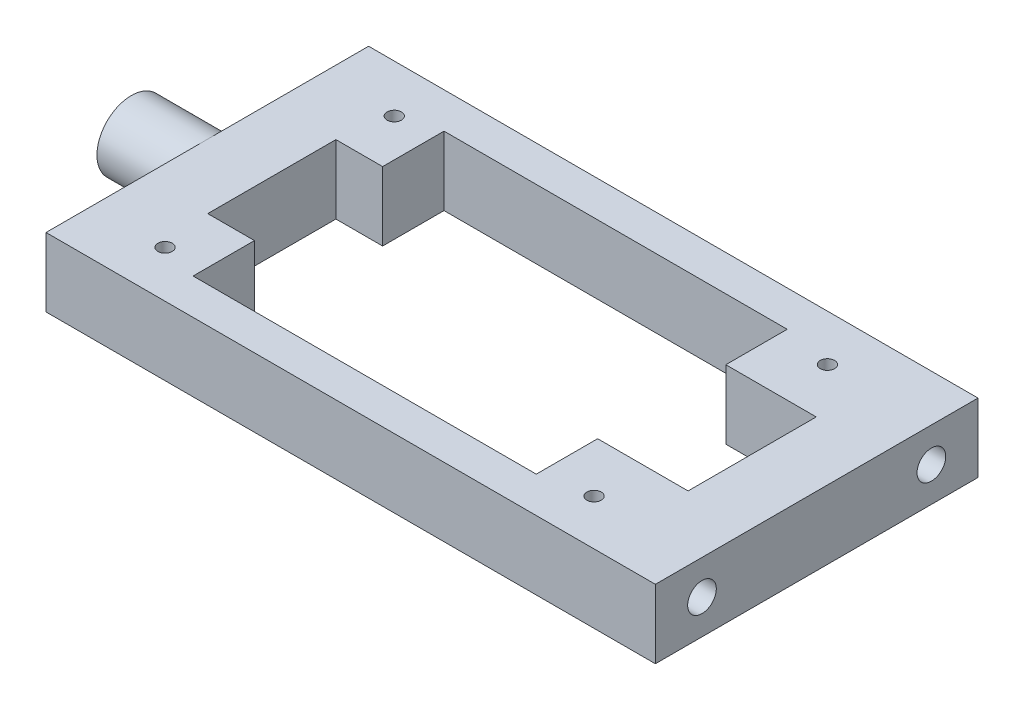
SolidWorks part; units mm, degrees
material "Prusament PETG"
ref_plane "Front Plane" through (0, 0, 0) normal (0, 0, 1) x (1, 0, 0)
ref_plane "Top Plane" through (0, 0, 0) normal (0, 1, 0) x (1, 0, 0)
ref_plane "Right Plane" through (0, 0, 0) normal (1, 0, 0) x (0, 0, -1)
sketch "Sketch1" plane through (0, 0, 0) normal (0, 0, 1) x (1, 0, 0)
  line L0 (0, 0) -> (0, 3.2946) construction
  line L1 (0, 0) -> (-16.8158, 0) construction
  line L6 (-32.9129, 10) -> (-22.9129, 10)
  line L7 (-32.9129, -10) -> (-22.9129, -10)
  arc A0 (-22.9129, 10) -> (-22.9129, -10) centre (0, 0) ccw
  arc A1 (-32.9129, 10) -> (-32.9129, -10) centre (0, 0) ccw
  dimension "D1" = 25
  dimension "D2" = 10
  dimension "D3" = 20
revolve "Revolve1" add sketch "Sketch1" angle 360 about L0
ref_plane "Plane1" through (34.3985, 0, 0) normal (1, 0, 0) x (0, 0, -1)
ref_plane "Plane2" through (49.3985, 0, 0) normal (1, 0, 0) x (0, 0, -1)
sketch "Sketch4" plane through (49.3985, 0, 0) normal (1, 0, 0) x (0, 0, -1)
  circle A0 centre (0, 0) radius 5
  dimension "D1" = 10
sketch "Sketch7" plane through (0, 0, 0) normal (0, 0, 1) x (1, 0, 0)
  line L0 (0, 0) -> (0, 26.9064) construction
  line L1 (0, 0) -> (-95.8603, 0) construction
  line L2 (0, 60) -> (0, 50)
  line L3 (0, -50) -> (0, -60)
  arc A0 (0, 50) -> (0, -50) centre (0, 0) ccw
  arc A1 (0, 60) -> (0, -60) centre (0, 0) ccw
  dimension "D2" = 10
  dimension "D1" = 50
sketch "Sketch8" plane through (0, -10, 0) normal (0, -1, 0) x (1, 0, 0)
  circle A0 centre (0, 0) radius 35
  dimension "D1" = 70
extrude "Boss-Extrude3" add sketch "Sketch8" along normal blind 1
sketch "Sketch9" plane through (0, 0, 0) normal (1, 0, 0) x (0, 0, -1)
  circle A0 centre (0, 0) radius 5
  dimension "D1" = 10
extrude "Boss-Extrude4" add sketch "Sketch9" along normal blind 60 and the other way up to surface
sketch "Sketch10" plane through (60, 0, 0) normal (1, 0, 0) x (0, 0, -1)
  circle A0 centre (0, 0) radius 4
ref_plane "Plane3" through (39.2087, 0, 0) normal (-1, 0, 0) x (0, 0, 1)
extrude "Cut-Extrude2" cut sketch "Sketch10" against normal up to surface (20.7913 mm away)
ref_plane "Plane4" through (0, 0.1888, -4.9964) normal (0, 0.0378, -0.9993) x (-1, 0, 0)
sketch "Sketch11" plane through (0, 0.1888, -4.9964) normal (0, 0.0378, -0.9993) x (-1, 0, 0)
  circle A0 centre (-55, 0) radius 5 construction
  circle A1 centre (-55, 0) radius 1.5
  dimension "D1" = 3
extrude "Cut-Extrude3" cut sketch "Sketch11" against normal through all
sketch "Sketch12" plane through (0, -11, 0) normal (0, -1, 0) x (1, 0, 0)
  line L4 (-43, -22.5) -> (-43, 22.5)
  line L5 (-43, -22.5) -> (-16.3848, -22.5)
  line L6 (-43, 22.5) -> (-16.8415, 22.5)
  line L7 (35, -22.5) -> (35, 22.5)
  line L8 (-35, 0) -> (35, 0) construction
  line L9 (-16.3848, -28.9013) -> (16.3848, -28.9013)
  line L11 (-16.8415, 22.5) -> (-16.8415, 28.9866)
  line L12 (-16.8415, 28.9866) -> (16.8415, 28.9866)
  line L13 (16.8415, 22.5) -> (16.8415, 28.9866)
  line L14 (-16.3848, -28.9013) -> (-16.3848, -22.5)
  line L16 (16.3848, -28.9013) -> (16.3848, -22.5)
  line L17 (16.8415, 22.5) -> (35, 22.5)
  line L18 (16.3848, -22.5) -> (35, -22.5)
  point P0 (-32.9035, 15.9936)
  point P1 (-32.9035, -16.0064)
  point P2 (27.0965, -16.0064)
  point P4 (27.0965, 15.9936)
  point P29 (0, 0)
  dimension "D1" = 78
  dimension "D2" = 45
extrude "Boss-Extrude5" add sketch "Sketch12" against normal up to surface (21 mm away) up to face at (0, 10, -32.9129)
sketch "Sketch13" plane through (-43, 0, 0) normal (-1, 0, 0) x (0, 0, 1)
  line L1 (44.4415, -11) -> (-44.4415, -11)
  line L2 (44.4415, -11) -> (44.4415, -5.4642)
  line L3 (44.4415, -5.4642) -> (-44.4415, -5.4642)
  line L4 (-44.4415, -11) -> (-44.4415, -5.4642)
  line L5 (22.5, -11) -> (-22.5, -11) construction
  line L6 (0, -11) -> (0, -5.4642) construction
  line L7 (0, -5.4642) -> (0, 10) construction
  line L8 (-22.5, 10) -> (22.5, 10) construction
  line L9 (0, 0) -> (-22.5, 0) construction
  line L10 (-22.5, 10) -> (-22.5, -10) construction
  line L11 (44.4415, 5.4642) -> (-44.4415, 5.4642)
  line L12 (-44.4415, 11) -> (-44.4415, 5.4642)
  line L13 (44.4415, 11) -> (-44.4415, 11)
  line L14 (44.4415, 11) -> (44.4415, 5.4642)
extrude "Cut-Extrude4" cut sketch "Sketch13" against normal through all
sketch "Sketch14" plane through (0, -5.4642, 0) normal (0, -1, 0) x (1, 0, 0)
  line L1 (27.0965, 15.9936) -> (-32.9035, 15.9936) construction
  line L2 (27.0965, 15.9936) -> (27.0965, -16.0064) construction
  line L3 (27.0965, -16.0064) -> (-32.9035, -16.0064) construction
  line L4 (-32.9035, 15.9936) -> (-32.9035, -16.0064) construction
  circle A0 centre (-32.9035, 15.9936) radius 1
  circle A1 centre (-32.7795, -15.854) radius 1
  circle A2 centre (27.0682, 16.122) radius 1
  circle A3 centre (27.45, -16.0449) radius 1
  dimension "D3" = 2
  dimension "D4" = 2
  dimension "D5" = 2
  dimension "D6" = 2
  dimension "D1" = 60
  dimension "D2" = 32
extrude "Cut-Extrude5" cut sketch "Sketch14" against normal through all
sketch "Sketch15" plane through (-43, 0, 0) normal (-1, 0, 0) x (0, 0, 1)
  line L1 (-37.9637, 5.4642) -> (37.2025, 5.4642)
  line L2 (-37.9637, 5.4642) -> (-37.9637, 5)
  line L3 (-37.9637, 5) -> (37.2025, 5)
  line L4 (37.2025, 5.4642) -> (37.2025, 5)
  line L5 (-37.6637, -5) -> (37.8003, -5)
  line L6 (-37.6637, -5) -> (-37.6637, -5.4642)
  line L7 (-37.6637, -5.4642) -> (37.8003, -5.4642)
  line L8 (37.8003, -5) -> (37.8003, -5.4642)
  line L9 (22.5, -5.4642) -> (-22.5, -5.4642) construction
  circle A0 centre (0, 0) radius 5 construction
  circle A1 centre (0, 0) radius 5 construction
extrude "Cut-Extrude6" cut sketch "Sketch15" against normal through all
sketch "Sketch16" plane through (-43, 0, 0) normal (-1, 0, 0) x (0, 0, 1)
  line L0 (22.5, 5) -> (22.5, -5) construction
  line L1 (-38.0201, 5) -> (36.8636, 5)
  line L2 (-38.0201, 5) -> (-38.0201, 4.8)
  line L3 (-38.0201, 4.8) -> (36.8636, 4.8)
  line L4 (36.8636, 5) -> (36.8636, 4.8)
  line L5 (-22.5, 0) -> (22.5, 0) construction
  line L6 (-22.5, 5) -> (-22.5, -5) construction
  line L7 (36.8636, -5) -> (36.8636, -4.8)
  line L8 (-38.0201, -5) -> (-38.0201, -4.8)
  line L9 (-38.0201, -5) -> (36.8636, -5)
  line L10 (-38.0201, -4.8) -> (36.8636, -4.8)
  line L11 (-22.5, 5) -> (-34.0332, 5) construction
  dimension "D1" = 0.2
extrude "Cut-Extrude7" cut sketch "Sketch16" against normal through all both and the other way through all
sketch "Sketch17" plane through (35, 0, 0) normal (1, 0, 0) x (0, 0, -1)
  line L0 (22.5, -4.8) -> (-22.5, -4.8)
  line L1 (22.5, -4.8) -> (22.5, 4.8706)
  line L2 (-22.5, -4.8) -> (-22.5, 4.8706)
  line L3 (22.5, 4.8706) -> (-22.5, 4.8706)
extrude "Cut-Extrude8" cut sketch "Sketch17" along normal up to surface (25 mm away) up to face at (60, 0, 0)
sketch "Sketch18" plane through (35, 0, 0) normal (1, 0, 0) x (0, 0, -1)
  line L0 (22.5, -4.8) -> (22.5, 4.8)
  line L1 (22.5, -4.8) -> (-22.6662, -4.8)
  line L2 (22.5, 4.8) -> (-22.6662, 4.8)
  line L3 (-22.6662, -4.8) -> (-22.6662, 4.8)
extrude "Boss-Extrude6" add sketch "Sketch18" along normal blind 7
sketch "Sketch19" plane through (42, 0, 0) normal (1, 0, 0) x (0, 0, -1)
  circle A0 centre (-16, 0.0112) radius 2
  circle A1 centre (16, 0.0112) radius 2
  dimension "D1" = 4
extrude "Cut-Extrude9" cut sketch "Sketch19" against normal blind 8.2
sketch "Sketch20" plane through (0, 4.8, 0) normal (0, 1, 0) x (1, 0, 0)
  line L0 (42, 22.5) -> (-43, 22.5)
  line L1 (42, 22.5) -> (42, 35.5488)
  line L2 (-43, 22.5) -> (-43, 35.5488)
  line L3 (42, 35.5488) -> (-43, 35.5488)
  line L4 (42.0002, -22.5) -> (-43, -22.5)
  line L5 (42.0002, -22.5) -> (42.0002, -36.4253)
  line L6 (-43, -22.5) -> (-43, -36.4253)
  line L7 (42.0002, -36.4253) -> (-43, -36.4253)
  line L8 (25.5728, -22.5) -> (35, -22.5) construction
  point P0 (0, 0)
extrude "Cut-Extrude10" cut sketch "Sketch20" against normal up to surface (9.6 mm away) up to face at (27.0682, -4.8, 17.122)
sketch "Sketch21" plane through (0, -4.8, 0) normal (0, -1, 0) x (1, 0, 0)
  line L0 (-110, 0) -> (42, 0) construction
  line L1 (42, 22.5) -> (42, -22.5) construction
  line L6 (-34, -8.938) -> (-34, 8.938)
  line L7 (-34, -8.938) -> (-27.4833, -8.938)
  line L8 (-34, 8.938) -> (-27.4833, 8.938)
  line L9 (33, -8.938) -> (33, 8.938)
  line L10 (-43, 22.5) -> (-43, 1.4) construction
  line L11 (-27.4833, -17.5) -> (-27.4833, -8.938)
  line L12 (-27.4833, -17.5) -> (20.3849, -17.5)
  line L13 (-27.4833, 17.5) -> (20.3849, 17.5)
  line L14 (20.3849, -17.5) -> (20.3849, -8.938)
  line L15 (-43, -22.5) -> (42, -22.5) construction
  line L16 (42, 22.5) -> (-43, 22.5) construction
  line L17 (20.3849, -8.938) -> (33, -8.938)
  line L18 (-27.4833, 8.938) -> (-27.4833, 17.5)
  line L19 (20.3849, 8.938) -> (33, 8.938)
  line L20 (20.3849, 8.938) -> (20.3849, 17.5)
  point P4 (-34, 0)
  dimension "D1" = 9
  dimension "D2" = 9
  dimension "D3" = 5
  dimension "D4" = 5
extrude "Cut-Extrude11" cut sketch "Sketch21" against normal through all
sketch "Sketch22" plane through (-53.5949, 0, 0) normal (-1, 0, 0) x (0, 0, 1)
  circle A0 centre (0, 0) radius 4.8
  circle A1 centre (0, 0) radius 5
extrude "Cut-Extrude12" cut sketch "Sketch22" against normal up to surface (10.5949 mm away) up to face at (-43, 0, -12.85)
equation "\"Ring_Thickness\"= 1cm"
equation "\"Ring_width\"= 2cm"
equation "\"Ring_Radius\"= 2.5cm"
equation "\"D1@Sketch1\"=\"Ring_Radius\""
equation "\"D2@Sketch1\"=\"Ring_Thickness\""
equation "\"D3@Sketch1\"=\"Ring_width\""
equation "\"Shaft_distance_from_ring_surface\"= 1.5cm"
equation "\"Shaft_Diameter\"= 1cm"
equation "\"D1@Sketch4\"=\"Shaft_Diameter\""
equation "\"D1@Plane2\"= \"Shaft_distance_from_ring_surface\""
equation "\"D1@Sketch7\"=\"Ring_Radius\"+\"Ring_Thickness\"+\"Shaft_distance_from_ring_surface\""
equation "\"D1@Sketch8\"=2*\"Ring_Radius\"+2*\"Ring_Thickness\""
equation "\"Drive_shaft_Length\"= 2cm"
equation "\"Drive_shaft_diameter\"= 10mm"
equation "\"D1@Sketch9\"=\"Drive_shaft_diameter\""
equation "\"fastener_hole_diameter\"= 3mm"
equation "\"D1@Sketch11\"=\"fastener_hole_diameter\""
equation "\"Pixhawk_Holes_Diameter\"= 2mm"
equation "\"D3@Sketch14\"=\"Pixhawk_Holes_Diameter\""
equation "\"D4@Sketch14\"=\"Pixhawk_Holes_Diameter\""
equation "\"D5@Sketch14\"=\"Pixhawk_Holes_Diameter\""
equation "\"D6@Sketch14\"=\"Pixhawk_Holes_Diameter\""
